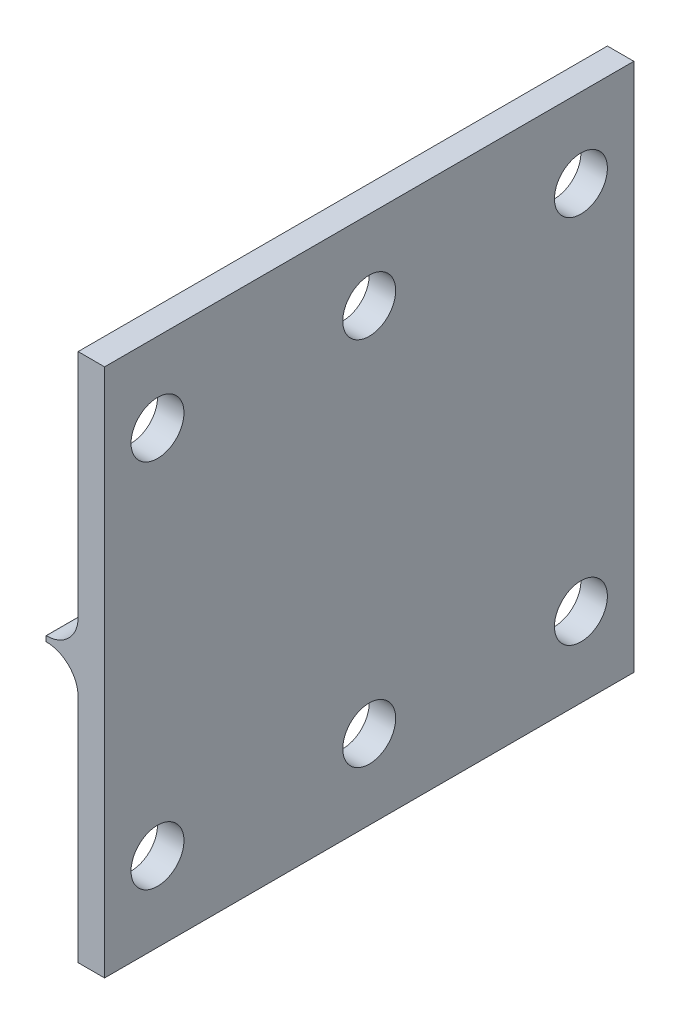
SolidWorks part; units mm, degrees
ref_plane "Front Plane" through (0, 0, 0) normal (0, 0, 1) x (1, 0, 0)
ref_plane "Top Plane" through (0, 0, 0) normal (0, 1, 0) x (1, 0, 0)
ref_plane "Right Plane" through (0, 0, 0) normal (1, 0, 0) x (0, 0, -1)
other "Configuration Table"
sketch "Sketch1" plane through (0, 0, 0) normal (0, 0, 1) x (1, 0, 0)
  line L0 (0, -275) -> (0, 275) construction
  line L1 (-25, 447.5295) -> (0, 447.5295)
  line L2 (-25, 447.5295) -> (-25, 230.0295)
  line L3 (-25, -52.4705) -> (0, -52.4705)
  line L4 (0, 447.5295) -> (0, -52.4705)
  line L5 (-55, 200.0295) -> (-55.1998, 200.0295)
  line L6 (-55.1998, 200.0295) -> (-55.1998, 195.0295)
  line L7 (-55.1998, 195.0295) -> (-55, 195.0295)
  line L8 (-25, 165.0295) -> (-25, 0)
  line L9 (55, 0) -> (-55, 0) construction
  line L11 (-25, 0) -> (-25, -52.4705)
  arc A0 (-55, 200.0295) -> (-25, 230.0295) centre (-55, 230.0295) ccw
  arc A1 (-25, 165.0295) -> (-55, 195.0295) centre (-55, 165.0295) ccw
  point P19 (-25, 195.0295)
  dimension "D3" = 30
  dimension "D4" = 30
  dimension "D1" = 25
  dimension "D2" = 500
  dimension "D5" = 5
  dimension "D6" = 247.5
extrude "Extrude1" add sketch "Sketch1" along normal blind 500
sketch "Sketch3" plane through (-25, 0, 0) normal (-1, 0, 0) x (0, 0, 1)
  line L0 (500, 165.0295) -> (500, -52.4705) construction
  line L1 (500, -52.4705) -> (0, -52.4705) construction
  line L2 (450, 22.5295) -> (250, 22.5295) construction
  line L3 (450, 22.5295) -> (450, 372.5295) construction
  circle A0 centre (450, 22.5295) radius 25
  circle A1 centre (250, 22.5295) radius 25
  circle A2 centre (50, 22.5295) radius 25
  circle A3 centre (450, 372.5295) radius 25
  circle A4 centre (250, 372.5295) radius 25
  circle A5 centre (50, 372.5295) radius 25
  dimension "D1" = 75
  dimension "D2" = 50
  dimension "D3" = 50
  dimension "D4" = 90
extrude "Cut-Extrude1" cut sketch "Sketch3" against normal through all
